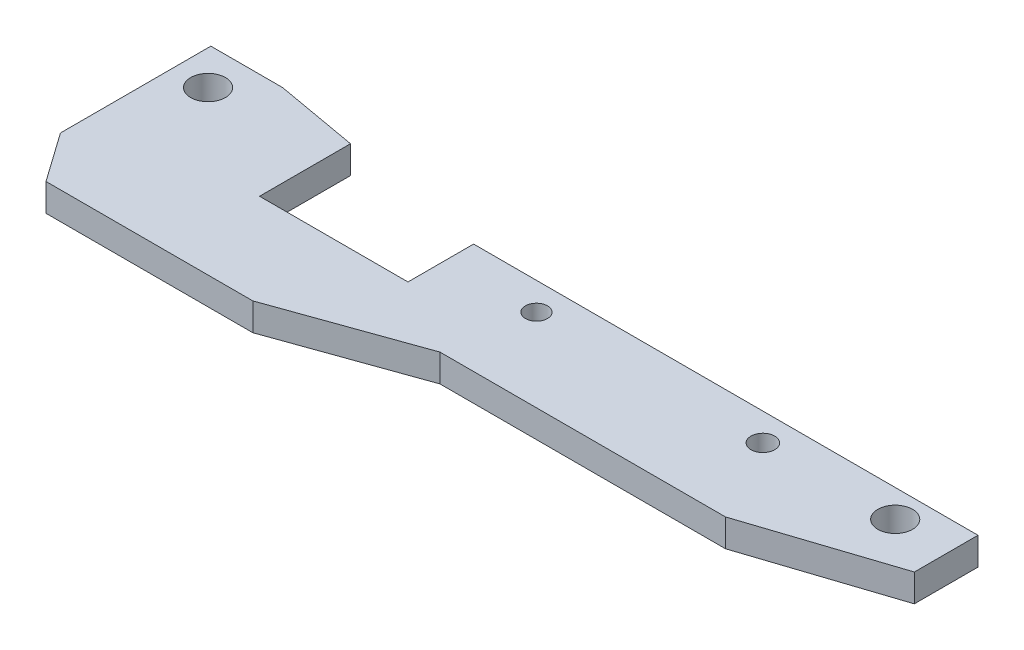
SolidWorks part; units mm, degrees
ref_plane "Front Plane" through (0, 0, 0) normal (0, 0, 1) x (1, 0, 0)
ref_plane "Top Plane" through (0, 0, 0) normal (0, 1, 0) x (1, 0, 0)
ref_plane "Right Plane" through (0, 0, 0) normal (1, 0, 0) x (0, 0, -1)
sketch "Sketch1" plane through (0, 0, 0) normal (0, 1, 0) x (1, 0, 0)
  line L0 (-13.7538, 8.7522) -> (-13.7538, 2.7832)
  line L1 (-13.7538, 2.7832) -> (-13.7538, -5.0908)
  line L2 (21.1765, -5.0908) -> (8.479, -9.6231)
  line L3 (33.8765, -5.0908) -> (21.1765, -5.0908)
  line L4 (60.5412, 5.0692) -> (60.5412, -0.0108)
  line L5 (-13.7538, 8.7522) -> (-7.1498, 8.7522)
  line L6 (-7.1498, 8.7522) -> (13.5671, 5.0692)
  line L7 (13.5671, 5.0692) -> (25.6162, 5.0692)
  line L8 (60.5412, -0.0108) -> (60.5412, -0.7896)
  line L9 (47.4555, -5.0908) -> (33.8765, -5.0908)
  line L10 (37.0462, 5.0692) -> (25.6162, 5.0692)
  line L11 (60.5412, -0.7896) -> (47.4555, -5.0908)
  line L12 (8.479, -9.6231) -> (-10.5513, -9.6231)
  line L13 (25.6162, 5.0692) -> (25.6162, -0.0108) construction
  line L14 (-10.5513, -9.6231) -> (-13.7538, -5.0908)
  line L15 (37.0462, -0.0108) -> (37.0462, 5.0692) construction
  line L16 (25.6162, -0.0108) -> (37.0462, -0.0108) construction
  line L17 (37.0462, 5.0692) -> (60.5412, 5.0692)
  circle A0 centre (22.4412, 2.5292) radius 1.016
  circle A1 centre (55.4612, 2.5292) radius 1.6
  circle A2 centre (-10.5788, 5.3232) radius 1.6
  circle A3 centre (43.2781, 2.5292) radius 1.0922
  dimension "D1" = 5.969
  dimension "D2" = 33.02
  dimension "D6" = 66.04
  dimension "D8" = 3.429
  dimension "D5" = 3.175
  dimension "D9" = 5.08
  dimension "D19" = 2.1844
  dimension "D3" = 6.604
  dimension "D4" = 5.08
  dimension "D11" = 11.43
  dimension "D18" = 20.7169
  dimension "D20" = 1.173
  dimension "D23" = 3.175
extrude "Boss-Extrude1" add sketch "Sketch1" along normal blind 2.54
sketch "Sketch2" plane through (0, 0, 0) normal (0, -1, 0) x (1, 0, 0)
  line L1 (14.1153, 0.9731) -> (0.4532, 0.9731)
  line L2 (14.1153, 0.9731) -> (14.1153, -8.7995)
  line L3 (14.1153, -8.7995) -> (0.4532, -8.7995)
  line L4 (0.4532, 0.9731) -> (0.4532, -8.7995)
extrude "Cut-Extrude1" cut sketch "Sketch2" against normal blind 2.54
